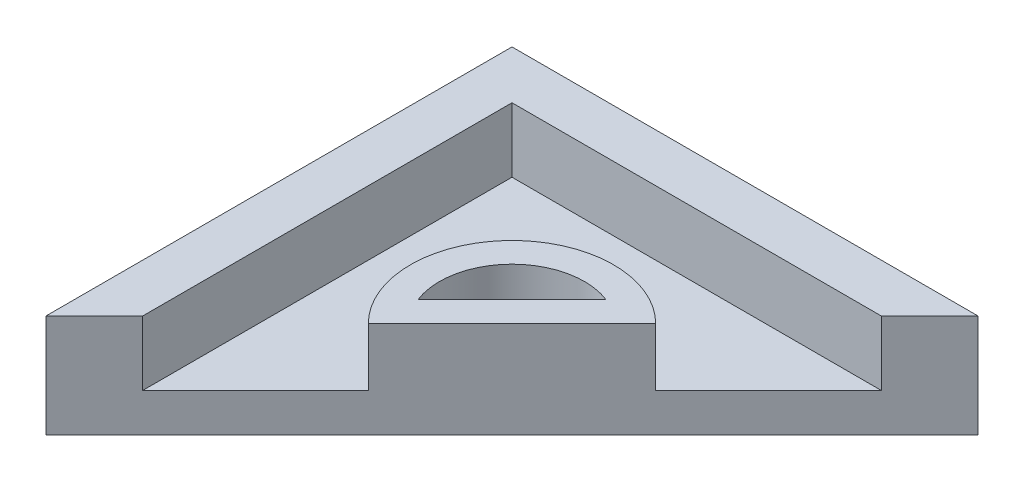
SolidWorks part; units mm, degrees
ref_plane "Front Plane" through (0, 0, 0) normal (0, 0, 1) x (1, 0, 0)
ref_plane "Top Plane" through (0, 0, 0) normal (0, 1, 0) x (1, 0, 0)
ref_plane "Right Plane" through (0, 0, 0) normal (1, 0, 0) x (0, 0, -1)
sketch "Sketch1" plane through (0, 0, 0) normal (0, 1, 0) x (1, 0, 0)
  line L0 (0, 0) -> (14.45, 0)
  line L1 (14.45, 0) -> (0, -14.45)
  line L2 (0, -14.45) -> (0, 0)
  dimension "D1" = 14.45
  dimension "D2" = 14.45
extrude "Boss-Extrude1" add sketch "Sketch1" against normal blind 1.2
sketch "Sketch2" plane through (0, 0, 0) normal (0, 1, 0) x (1, 0, 0)
  line L0 (0, 0) -> (14.45, 0)
  line L1 (14.45, 0) -> (12.95, -1.5)
  line L2 (0, -14.45) -> (14.45, 0) construction
  line L3 (12.95, -1.5) -> (1.5, -1.5)
  line L4 (1.5, -1.5) -> (1.5, -12.95)
  line L5 (1.5, -12.95) -> (0, -14.45)
  line L6 (0, 0) -> (0, -14.45) construction
  line L7 (0, -14.45) -> (0, 0)
  dimension "D1" = 1.5
  dimension "D2" = 1.5
extrude "Boss-Extrude2" add sketch "Sketch2" along normal blind 2
sketch "Sketch3" plane through (0, 0, 0) normal (0, 1, 0) x (1, 0, 0)
  line L1 (1.5, -12.95) -> (12.95, -1.5) construction
  line L2 (4.9976, -9.4524) -> (9.4524, -4.9976)
  line L3 (5.1304, -8.0468) -> (8.0468, -5.1304)
  arc A1 (4.9976, -9.4524) -> (9.4524, -4.9976) centre (7.225, -7.225) cw
  arc A2 (5.1304, -8.0468) -> (8.0468, -5.1304) centre (7.225, -7.225) cw
  dimension "D1" = 3.15
  dimension "D2" = 2.25
  dimension "D3" = 0.9
extrude "Boss-Extrude3" add sketch "Sketch3" along normal offset from surface (1.8 mm away) 0.2 up to face at (5.0667, 2, 5.0667)
